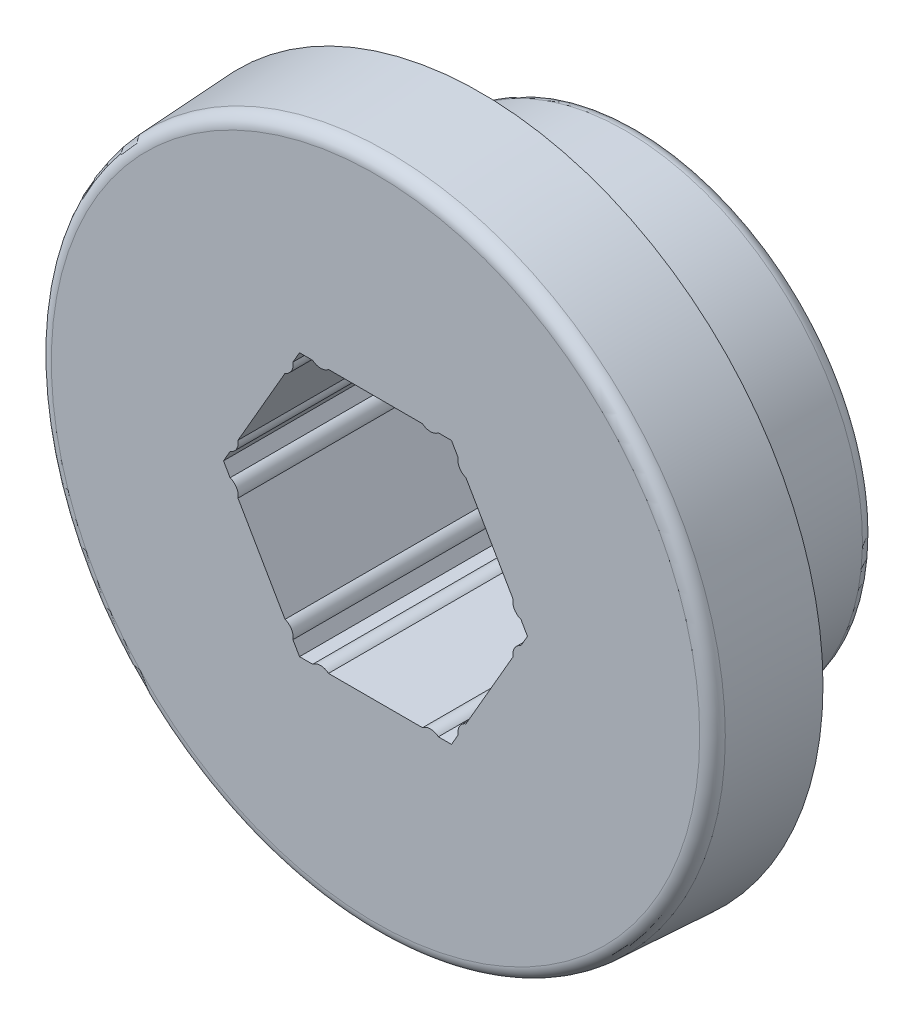
SolidWorks part; units mm, degrees
ref_plane "Front Plane" through (0, 0, 0) normal (0, 0, 1) x (1, 0, 0)
ref_plane "Top Plane" through (0, 0, 0) normal (0, 1, 0) x (1, 0, 0)
ref_plane "Right Plane" through (0, 0, 0) normal (1, 0, 0) x (0, 0, -1)
sketch "Sketch1" plane through (0, 0, 0) normal (0, 1, 0) x (1, 0, 0)
  line L0 (6.5, 0) -> (0, 0)
  line L1 (0, 0) -> (0, -2)
  line L2 (0, -2) -> (6.3952, -2)
  line L3 (6.3952, -2) -> (6.5, 0)
  line L4 (0, 0) -> (0, -2) construction
revolve "Revolve1" add sketch "Sketch1" angle 360 about L4
sketch "Sketch2" plane through (0, 0, 0) normal (0, 0, -1) x (-1, 0, 0)
  circle A0 centre (0, 0) radius 4.5
extrude "Boss-Extrude1" add sketch "Sketch2" along normal blind 3
sketch "Sketch3" plane through (0, 0, 2) normal (0, 0, 1) x (1, 0, 0)
  line L0 (1.5684, 2.2835) -> (1.4434, 2.5)
  line L1 (1.4434, 2.5) -> (1.1934, 2.5)
  line L2 (0.8934, 2.5) -> (-0.8934, 2.5)
  line L3 (-1.1934, 2.5) -> (-1.4434, 2.5)
  line L4 (-1.4434, 2.5) -> (-1.5684, 2.2835)
  line L5 (-1.7184, 2.0237) -> (-2.6118, 0.4763)
  line L6 (-2.7618, 0.2165) -> (-2.8868, 0)
  line L7 (-2.8868, 0) -> (-2.7618, -0.2165)
  line L8 (-2.6118, -0.4763) -> (-1.7184, -2.0237)
  line L9 (-1.5684, -2.2835) -> (-1.4434, -2.5)
  line L10 (-1.4434, -2.5) -> (-1.1934, -2.5)
  line L11 (-0.8934, -2.5) -> (0.8934, -2.5)
  line L12 (1.1934, -2.5) -> (1.4434, -2.5)
  line L13 (1.4434, -2.5) -> (1.5684, -2.2835)
  line L14 (1.7184, -2.0237) -> (2.6118, -0.4763)
  line L15 (2.7618, -0.2165) -> (2.8868, 0)
  line L16 (2.8868, 0) -> (2.7618, 0.2165)
  line L17 (2.6118, 0.4763) -> (1.7184, 2.0237)
  arc A0 (1.7184, 2.0237) -> (1.5684, 2.2835) centre (1.7967, 2.2421) cw
  arc A1 (1.1934, 2.5) -> (0.8934, 2.5) centre (1.0434, 2.677) cw
  arc A2 (-0.8934, 2.5) -> (-1.1934, 2.5) centre (-1.0434, 2.677) cw
  arc A3 (-1.5684, 2.2835) -> (-1.7184, 2.0237) centre (-1.7967, 2.2421) cw
  arc A4 (-2.6118, 0.4763) -> (-2.7618, 0.2165) centre (-2.8401, 0.4349) cw
  arc A5 (-2.7618, -0.2165) -> (-2.6118, -0.4763) centre (-2.8401, -0.4349) cw
  arc A6 (-1.7184, -2.0237) -> (-1.5684, -2.2835) centre (-1.7967, -2.2421) cw
  arc A7 (-1.1934, -2.5) -> (-0.8934, -2.5) centre (-1.0434, -2.677) cw
  arc A8 (0.8934, -2.5) -> (1.1934, -2.5) centre (1.0434, -2.677) cw
  arc A9 (1.5684, -2.2835) -> (1.7184, -2.0237) centre (1.7967, -2.2421) cw
  arc A10 (2.6118, -0.4763) -> (2.7618, -0.2165) centre (2.8401, -0.4349) cw
  arc A11 (2.7618, 0.2165) -> (2.6118, 0.4763) centre (2.8401, 0.4349) cw
extrude "Cut-Extrude1" cut sketch "Sketch3" against normal through all
fillet "Fillet1" radius 0.25 2 edges at (6.3952, 0, 2) (0, 4.5, -3)
